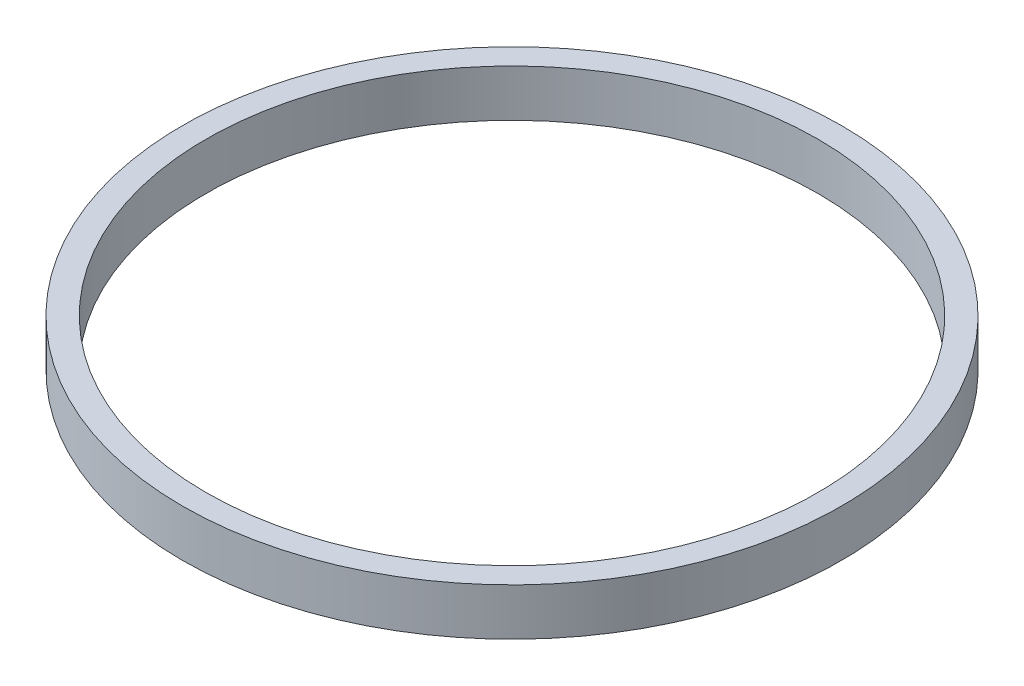
SolidWorks part; units mm, degrees
ref_plane "Ön Düzlem" through (0, 0, 0) normal (0, 0, 1) x (1, 0, 0)
ref_plane "Üst Düzlem" through (0, 0, 0) normal (0, 1, 0) x (1, 0, 0)
ref_plane "Sağ Düzlem" through (0, 0, 0) normal (1, 0, 0) x (0, 0, -1)
sketch "Çizim1" plane through (0, 0, 0) normal (0, 1, 0) x (1, 0, 0)
  circle A0 centre (0, 0) radius 65
  circle A1 centre (0, 0) radius 70
  dimension "D1" = 5
  dimension "D2" = 140
extrude "Yükseklik-Ekstrüzyon1" add sketch "Çizim1" along normal blind 10
